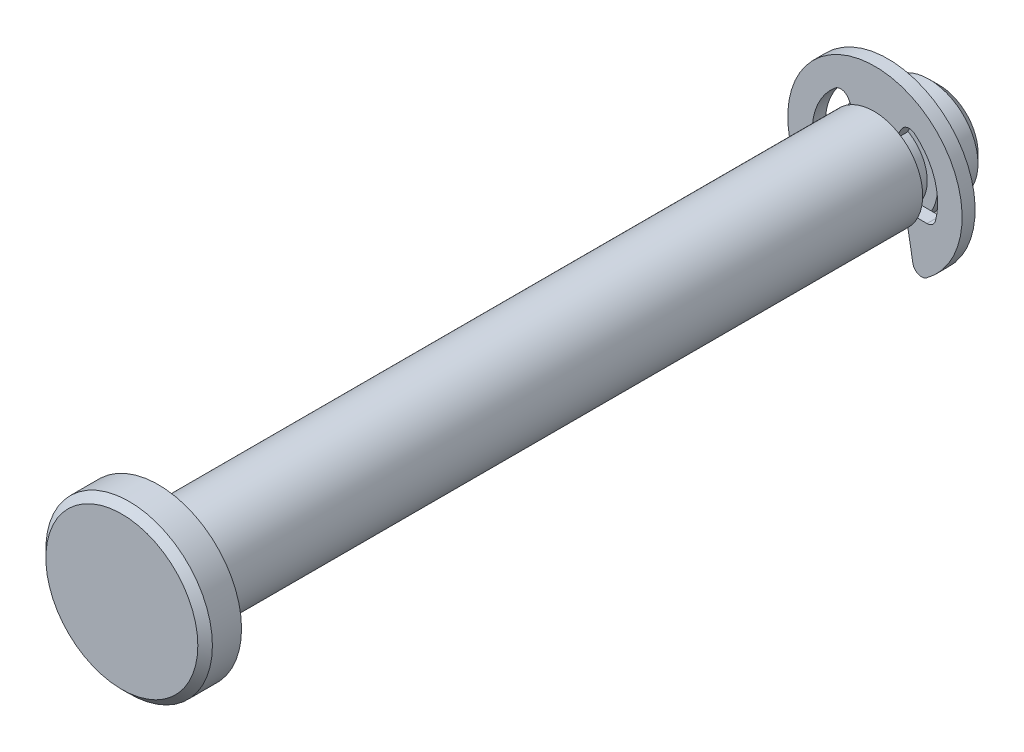
SolidWorks part; units mm, degrees
ref_plane "Front" through (0, 0, 0) normal (0, 0, 1) x (1, 0, 0)
ref_plane "Top" through (0, 0, 0) normal (0, 1, 0) x (1, 0, 0)
ref_plane "Right" through (0, 0, 0) normal (1, 0, 0) x (0, 0, -1)
sketch "Sketch2" plane through (0, 0, 0) normal (0, 0, 1) x (1, 0, 0)
  circle A0 centre (0, 0) radius 2.3813
  point P3 (0, 2.3813)
  point P4 (0, -2.3813)
  dimension "dia" = 4.7625
extrude "Extrude1" add sketch "Sketch2" along normal mid plane 38.1
sketch "Sketch3" plane through (0, 0, 0) normal (1, 0, 0) x (0, 0, -1)
  line L0 (19.05, 2.3813) -> (-19.05, 2.3813) construction
  line L1 (15.875, 2.3812) -> (16.6116, 2.3813)
  line L2 (15.875, 2.3812) -> (15.875, 1.8669)
  line L3 (15.875, 1.8669) -> (16.6116, 1.8669)
  line L4 (16.6116, 2.3813) -> (16.6116, 1.8669)
  line L5 (-19.05, 2.3813) -> (-19.05, -2.3813) construction
  line L10 (16.6116, 1.8669) -> (16.6116, -1.8669) construction
  point P11 (16.6116, 0)
  point P14 (16.2433, 2.3813)
  dimension "groove wd" = 0.7366
  dimension "groove dia" = 3.7338
  dimension "usable lg" = 34.925
revolve "Cut-Revolve1" cut sketch "Sketch3" angle 360 about axis through (0, 0, 19.05) along (0, 0, -1)
sketch "Sketch8" plane through (0, 0, 19.05) normal (0, 0, 1) x (1, 0, 0)
  circle A0 centre (0, 0) radius 4.064
  dimension "head dia" = 8.128
extrude "Extrude6" add sketch "Sketch8" along normal blind 1.778
chamfer "Chamfer2" distance 0.3556 angle 45 1 edges at (4.064, 0, 20.828)
ref_plane "Plane1" through (0, 0, -16.2433) normal (0, 0, 1) x (1, 0, 0)
sketch "Sketch4" plane through (0, 0, -16.2433) normal (0, 0, 1) x (1, 0, 0)
  line L0 (0, 1.8669) -> (0, -1.8669) construction
  circle A0 centre (0, 0) radius 4.2545
  circle A1 centre (0, 0) radius 1.8669
  dimension "ring dia" = 8.509
extrude "Extrude2" add sketch "Sketch4" along normal mid plane 0.635 separate body
sketch "Sketch5" plane through (0, 0, 0) normal (0, 0, 1) x (1, 0, 0)
  line L0 (0, 4.2545) -> (0, 1.8669) construction
  line L1 (-1.5304, 2.6506) -> (0, 0)
  line L2 (-2.8484, -1.1201) -> (-1.4935, -1.1201)
  line L3 (0, 0) -> (1.5304, 2.6506)
  line L4 (-1.4935, -1.1201) -> (-1.9617, -3.7753)
  line L5 (1.4935, -1.1201) -> (1.9617, -3.7753)
  line L6 (1.4935, -1.1201) -> (2.8484, -1.1201)
  arc A0 (-1.5304, 2.6506) -> (-2.8484, -1.1201) centre (0, 0) ccw
  circle A1 centre (0, 0) radius 4.2545 construction
  circle A2 centre (0, 0) radius 1.8669 construction
  arc A3 (2.8484, -1.1201) -> (1.5304, 2.6506) centre (0, 0) ccw
  arc A4 (-1.9617, -3.7753) -> (1.9617, -3.7753) centre (0, 0) ccw
  circle A5 centre (0, 0) radius 1.8669 construction
  point P10 (0, 3.0607)
  dimension "D1" = 30
  dimension "D2" = 10
  dimension "D3" = 1.1201
extrude "Extrude4" cut sketch "Sketch5" against normal through all
sketch "Sketch6" plane through (0, 0, -15.9258) normal (0, 0, 1) x (1, 0, 0)
  line L0 (-0.9335, 1.6168) -> (0.9335, 1.6168)
  circle A0 centre (0, 0) radius 1.8669 construction
  arc A1 (0.9335, 1.6168) -> (-0.9335, 1.6168) centre (0, 0) ccw
extrude "Extrude5" add sketch "Sketch6" against normal up to surface (0.635 mm away) up to face at (0, 0.5273, -16.5608)
fillet "Fillet1" radius 0.4254 6 edges at (1.9617, -3.7753, -16.2433) (-1.9617, -3.7753, -16.2433) (2.8484, -1.1201, -16.2433) (1.5304, 2.6506, -16.2433) (-1.5304, 2.6506, -16.2433) (-2.8484, -1.1201, -16.2433)
chamfer "Chamfer1" distance 0.4763 angle 45 1 edges at (2.3813, 0, -19.05)
sketch "Sketch7" plane through (0, 0, 0) normal (1, 0, 0) x (0, 0, -1)
  line L0 (16.5608, 4.2545) -> (15.9258, 4.2545) construction
  line L1 (19.05, -2.3813) -> (19.05, 2.3813) construction
  line L2 (15.9258, -3.5079) -> (16.5608, -3.5079) construction
  line L3 (-20.828, 3.7084) -> (-20.828, -3.7084) construction
  point P0 (16.6116, -3.5079)
  point P1 (19.05, 2.3813)
  point P2 (-20.828, 4.064)
  point P6 (15.875, 4.2545)
  point P7 (19.05, -2.3813)
  point P12 (-19.05, 4.064)
  point P16 (15.875, -3.5079)
equation "\"D1@Chamfer1\" = \"dia@Sketch2\" * .1"
equation "\"D1@Fillet1\" = \"ring dia@Sketch4\" * .05"
equation "\"D3@Sketch5\" = \"groove dia@Sketch3\" * .3"
equation "\"D1@Chamfer2\" = \"head ht@Extrude6\" * .2"
